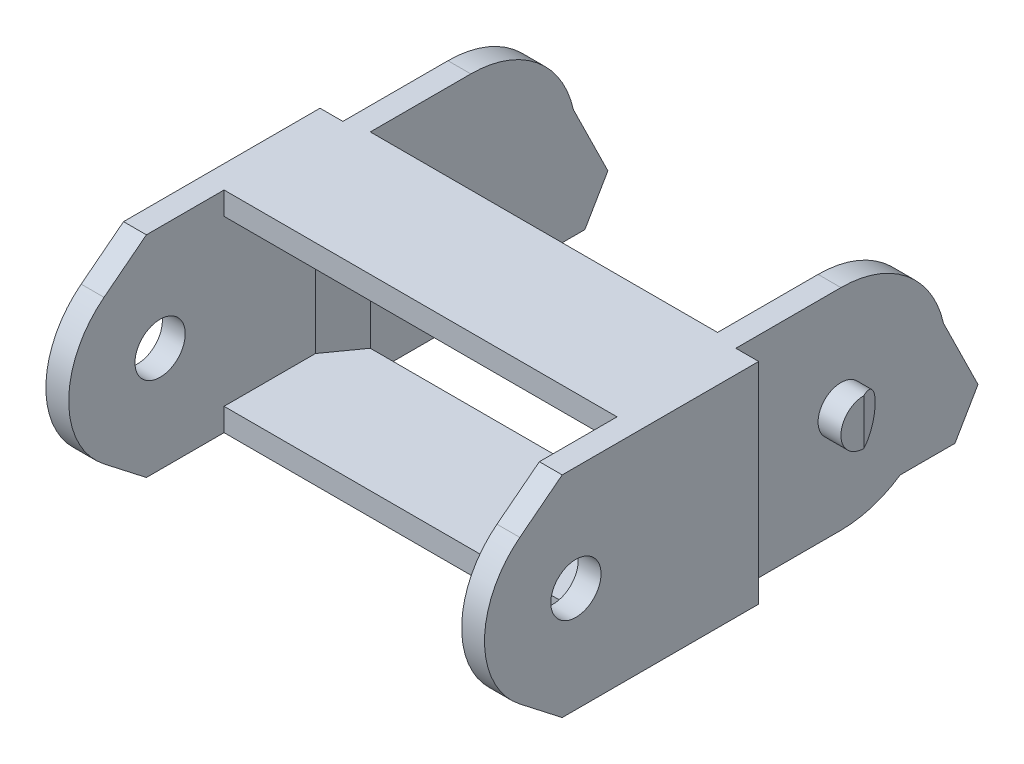
SolidWorks part; units mm, degrees
ref_plane "Front Plane" through (0, 0, 0) normal (0, 0, 1) x (1, 0, 0)
ref_plane "Top Plane" through (0, 0, 0) normal (0, 1, 0) x (1, 0, 0)
ref_plane "Right Plane" through (0, 0, 0) normal (1, 0, 0) x (0, 0, -1)
sketch "Sketch1" plane through (0, 0, 0) normal (1, 0, 0) x (0, 0, -1)
  line L0 (0, 11.5) -> (0, -11.5) construction
  line L1 (16.5, -11.5) -> (-16.5, -11.5)
  line L2 (16.5, -11.5) -> (16.5, 11.5) construction
  line L3 (16.5, 11.5) -> (-16.5, 11.5)
  line L5 (-21.1373, 7.8951) -> (-16.5, 11.5)
  line L6 (-16.5, -11.5) -> (-21.1373, -7.8951)
  line L7 (-16.5, 11.5) -> (-16.5, -11.5) construction
  line L8 (-15, 0) -> (0, 0) construction
  arc A1 (-21.1373, 7.8951) -> (-21.1373, -7.8951) centre (-15, 0) ccw
  arc A2 (16.5, -11.5) -> (16.5, 11.5) centre (16.5, 0) ccw
  point P0 (0, 0)
  dimension "D1" = 10
  dimension "D2" = 1.5
  dimension "D3" = 23
  dimension "D4" = 15
extrude "Boss-Extrude1" add sketch "Sketch1" along normal mid plane 48
sketch "Sketch2" plane through (24, 0, 0) normal (1, 0, 0) x (0, 0, -1)
  line L0 (16.5, 11.5) -> (-16.5, 11.5) construction
  line L1 (5, 11.5) -> (28, 11.5)
  line L2 (5, 11.5) -> (5, -11.5)
  line L3 (5, -11.5) -> (28, -11.5)
  line L4 (28, 11.5) -> (28, -11.5)
  line L5 (-16.5, -11.5) -> (16.5, -11.5) construction
  arc A0 (16.5, -11.5) -> (16.5, 11.5) centre (16.5, 0) ccw construction
  arc A1 (-21.1373, 7.8951) -> (-21.1373, -7.8951) centre (-15, 0) ccw construction
  dimension "D1" = 30
extrude "Cut-Extrude1" cut sketch "Sketch2" against normal blind 2.5
mirror "Mirror1" about plane through (0, 0, 0) normal (1, 0, 0) of "Cut-Extrude1"
sketch "Sketch4" plane through (0, 11.5, 0) normal (0, 1, 0) x (1, 0, 0)
  line L0 (0, 0) -> (0, -8) construction
  line L1 (-21.5, -8) -> (21.5, -8)
  line L2 (-21.5, -8) -> (-21.5, -25)
  line L3 (-21.5, -25) -> (21.5, -25)
  line L4 (21.5, -8) -> (21.5, -25)
  line L5 (-21.5, 16.5) -> (-21.5, 5) construction
  line L6 (-24, -25) -> (24, -25) construction
  dimension "D1" = 17
extrude "Cut-Extrude2" cut sketch "Sketch4" against normal through all
sketch "Sketch5" plane through (0, 11.5, 0) normal (0, 1, 0) x (1, 0, 0)
  line L0 (21.5, -8) -> (-21.5, -8) construction
  line L1 (-19, 5.5) -> (19, 5.5)
  line L2 (-19, 5.5) -> (-19, 28)
  line L3 (-19, 28) -> (19, 28)
  line L4 (19, 5.5) -> (19, 28)
  line L5 (0, 5.5) -> (0, 0) construction
  line L6 (-21.5, 16.5) -> (-21.5, 5) construction
  line L7 (21.5, 28) -> (-21.5, 28) construction
  dimension "D1" = 13.5
  dimension "D2" = 2.5
extrude "Cut-Extrude3" cut sketch "Sketch5" against normal through all
sketch "Sketch6" plane through (0, 0, 0) normal (0, 1, 0) x (1, 0, 0)
  line L0 (-19, 5.5) -> (-21.5, 2)
  line L1 (-21.5, 2) -> (-21.5, -8)
  line L2 (-21.5, -8) -> (21.5, -8)
  line L3 (21.5, -8) -> (21.5, 2)
  line L4 (21.5, 2) -> (19, 5.5)
  line L5 (-19, 5.5) -> (19, 5.5) construction
  line L6 (19, 5.5) -> (-19, 5.5)
  line L7 (-21.5, 2) -> (21.5, 2) construction
  dimension "D1" = 3.5
extrude "Cut-Extrude4" cut sketch "Sketch6" against normal mid plane 18
sketch "Sketch7" plane through (24, 0, 0) normal (1, 0, 0) x (0, 0, -1)
  circle A0 centre (-15, 0) radius 2.75
  dimension "D1" = 5.5
extrude "Cut-Extrude5" cut sketch "Sketch7" against normal through all
sketch "Sketch8" plane through (21.5, 0, 0) normal (1, 0, 0) x (0, 0, -1)
  circle A0 centre (16.5, 0) radius 2.5
  dimension "D1" = 5
extrude "Boss-Extrude2" add sketch "Sketch8" along normal through all
sketch "Sketch9" plane through (0, 11.5, 0) normal (0, 1, 0) x (1, 0, 0)
  line L0 (22.75, 19) -> (24, 16.5)
  line L1 (24, 19) -> (21.5, 19) construction
  line L2 (24, 14) -> (24, 19) construction
  line L3 (24, 16.5) -> (24, 19)
  line L4 (24, 19) -> (22.75, 19)
extrude "Cut-Extrude6" cut sketch "Sketch9" against normal through all
sketch "Sketch10" plane through (21.5, 0, 0) normal (1, 0, 0) x (0, 0, -1)
  line L0 (27.725, 2.5) -> (31.5, -5.181)
  line L1 (31.5, -5.181) -> (28.9807, -9.5)
  line L2 (28.9807, -9.5) -> (22.9807, -9.5)
  line L4 (5, -11.5) -> (16.5, -11.5) construction
  line L5 (16.5, 2.5) -> (16.5, -2.5) construction
  line L6 (16.5, 2.5) -> (27.725, 2.5) construction
  arc A0 (16.5, -11.5) -> (16.5, 11.5) centre (16.5, 0) ccw construction
  arc A1 (22.9807, -9.5) -> (27.725, 2.5) centre (16.5, 0) ccw
  dimension "D1" = 2
  dimension "D2" = 15
  dimension "D3" = 5
  dimension "D4" = 6
extrude "Boss-Extrude4" add sketch "Sketch10" against normal blind 2.5
mirror "Mirror2" about plane through (0, 0, 0) normal (1, 0, 0) of "Boss-Extrude4", "Boss-Extrude2", "Cut-Extrude6"
